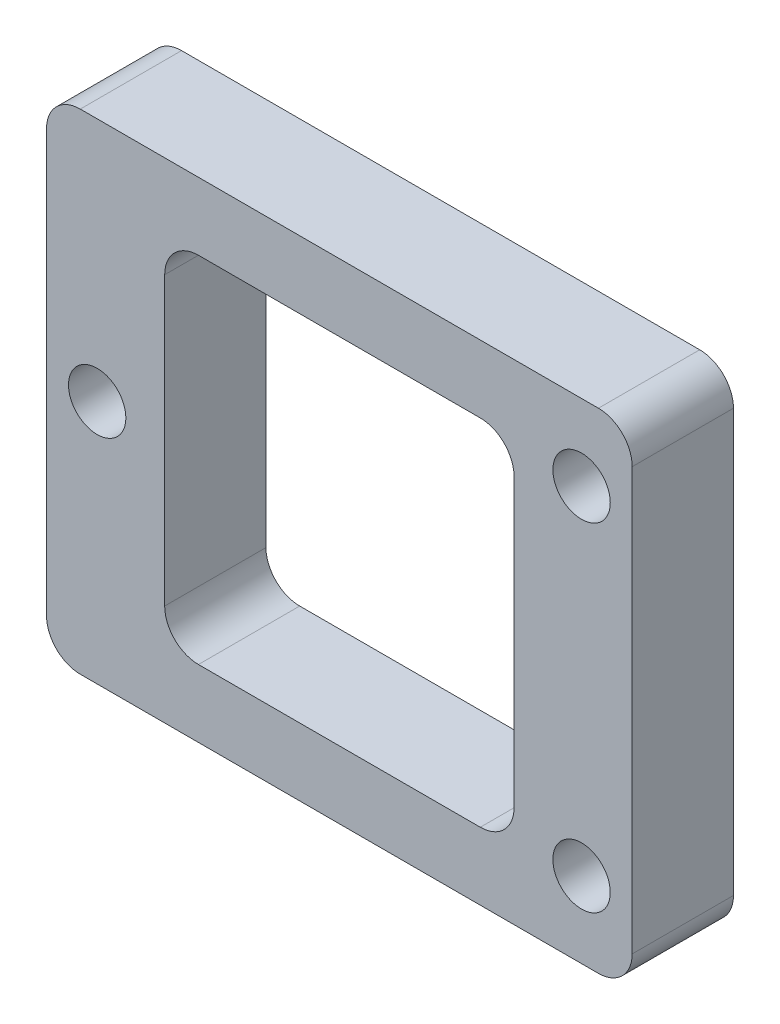
SolidWorks part; units mm, degrees
material "ABS"
ref_plane "前视基准面" through (0, 0, 0) normal (0, 0, 1) x (1, 0, 0)
ref_plane "上视基准面" through (0, 0, 0) normal (0, 1, 0) x (1, 0, 0)
ref_plane "右视基准面" through (0, 0, 0) normal (1, 0, 0) x (0, 0, -1)
other "Configuration Table"
sketch "草图1" plane through (0, 0, 0) normal (0, 0, 1) x (1, 0, 0)
  line L1 (-17.35, -14.5) -> (17.35, -14.5)
  line L2 (-17.35, -14.5) -> (-17.35, 14.5)
  line L3 (-17.35, 14.5) -> (17.35, 14.5)
  line L4 (17.35, -14.5) -> (17.35, 14.5)
  line L5 (-17.35, -14.5) -> (17.35, 14.5) construction
  line L6 (-17.35, 14.5) -> (17.35, -14.5) construction
  point P0 (0, 0)
  dimension "D1" = 34.7
  dimension "D2" = 29
extrude "凸台-拉伸1" add sketch "草图1" along normal blind 6
sketch "草图2" plane through (0, 0, 6) normal (0, 0, 1) x (1, 0, 0)
  circle A0 centre (14.35, -10) radius 1.5 construction
  circle A1 centre (-14.35, 0) radius 1.5 construction
  circle A2 centre (14.35, 10) radius 1.5 construction
  circle A3 centre (14.35, -10) radius 1.5 construction
  circle A4 centre (-14.35, 0) radius 1.5 construction
  circle A5 centre (14.35, 10) radius 1.5 construction
  circle A6 centre (14.35, -10) radius 1.7
  circle A7 centre (-14.35, 0) radius 1.7
  circle A8 centre (14.35, 10) radius 1.7
  dimension "D1" = 3.4
extrude "切除-拉伸1" cut sketch "草图2" against normal blind 25
sketch "草图3" plane through (0, 0, 6) normal (0, 0, 1) x (1, 0, 0)
  line L0 (17.35, 14.5) -> (-17.35, 14.5) construction
  line L1 (-10.35, -10.5) -> (10.35, -10.5)
  line L2 (-10.35, -10.5) -> (-10.35, 10.5)
  line L3 (-10.35, 10.5) -> (10.35, 10.5)
  line L4 (10.35, -10.5) -> (10.35, 10.5)
  line L5 (-10.35, -10.5) -> (10.35, 10.5) construction
  line L6 (-10.35, 10.5) -> (10.35, -10.5) construction
  line L7 (-17.35, -14.5) -> (17.35, -14.5) construction
  circle A0 centre (14.35, 10) radius 1.7 construction
  circle A1 centre (-14.35, 0) radius 1.7 construction
  point P0 (0, 0)
  point P11 (0, 0)
  dimension "D1" = 4
  dimension "D2" = 4
  dimension "D3" = 4
  dimension "D4" = 4
extrude "切除-拉伸2" cut sketch "草图3" against normal blind 10
fillet "圆角1" radius 2 4 edges at (-10.35, -10.5, 3) (-10.35, 10.5, 3) (10.35, 10.5, 3) (10.35, -10.5, 3)
fillet "圆角2" radius 2 4 edges at (17.35, -14.5, 3) (-17.35, -14.5, 3) (-17.35, 14.5, 3) (17.35, 14.5, 3)
equation "\"D4@草图3\"=\"D3@草图3\""
